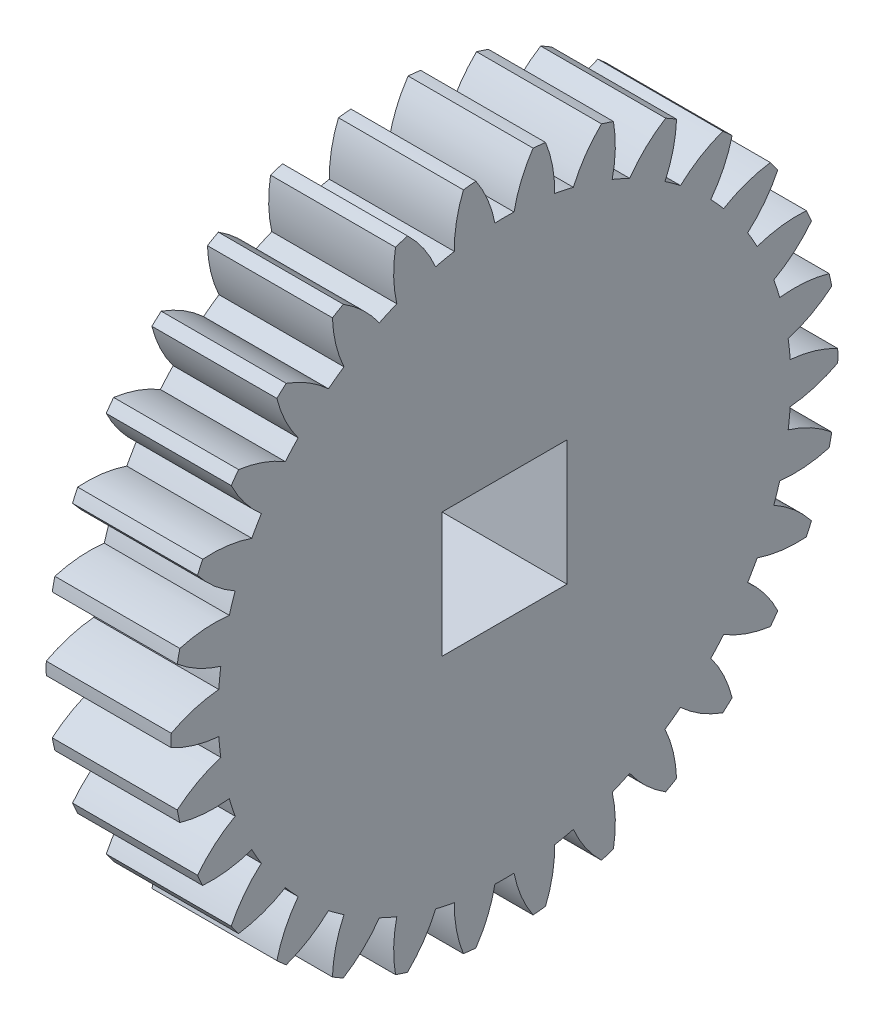
SolidWorks part; units mm, degrees
ref_plane "Plane1" through (0, 0, 0) normal (0, 0, 1) x (1, 0, 0)
ref_plane "Plane2" through (0, 0, 0) normal (0, 1, 0) x (1, 0, 0)
ref_plane "Plane3" through (0, 0, 0) normal (1, 0, 0) x (0, 0, -1)
sketch "HoldingSke" plane through (0, 0, 0) normal (0, 1, 0) x (1, 0, 0)
  line L0 (0, 0) -> (0.1732, -0.1)
  line L1 (-15, 0) -> (100, 0) construction
  line L2 (0, 0) -> (-2.1039, 2.3779)
  line L3 (0, 0) -> (-11.863, 4.5341)
  line L4 (0, 0) -> (7.479, 4.318)
  line L5 (0, 0) -> (-46.8476, -17.4728)
  line L6 (0, 0) -> (-13.2634, -8.9489)
  line L7 (-2.1039, 2.3779) -> (8.6586, 51.2059)
  line L8 (-76.2, 54.61) -> (-72.9, 54.61)
  line L9 (-71.009, 38.7566) -> (-53.1078, 45.2721)
  line L10 (-76.2, 71.12) -> (104.1128, 71.12)
  line L11 (0, 0) -> (-16, 0)
  line L12 (-76.2, 101.6) -> (-76.033, 101.6)
  line L13 (24.9733, 27.94) -> (52.9518, 28.4284)
  line L14 (24.9733, 27.94) -> (24.9743, 27.94)
  line L15 (24.9733, 27.94) -> (100.4006, 29.5858)
  line L16 (-63.627, -5) -> (-12.827, -5)
  circle A0 centre (0, 0) radius 13
  circle A1 centre (0, 0) radius 37.5
  circle A2 centre (0, 0) radius 37.5
  circle A3 centre (0, 0) radius 13
  dimension "MHD" = 75
  dimension "Hub_dia" = 75
  dimension "Bore" = 26
  dimension "MBD" = 26
  dimension "Num_teeth" = 30
  dimension "Pitch" = 0.2
  dimension "Overall_len" = 50
  dimension "Show_teeth" = 30
  dimension "Thickness" = 16
  dimension "OAL" = 50.0001
  dimension "T_dim" = 3.3
  dimension "Ap" = 20
  dimension "H" = 19.05
  dimension "Pitch_radius" = 180.3128
  dimension "Width" = 16
  dimension "Backlash" = 0.167
  dimension "Addendum_fac" = 1
  dimension "Dedendum_fac" = 1.25
  dimension "Clearance_fac" = 0.25
  dimension "Dedendum_add" = 0.001
  dimension "Module" = 5
sketch "BasProSke" plane through (0, 0, 0) normal (0, 1, 0) x (1, 0, 0)
  line L0 (-10, 0) -> (60, 0) construction
  line L1 (0, 0) -> (0, 80)
  line L2 (0, 0) -> (30, 0)
  line L3 (30, 0) -> (30, 80)
  line L4 (30, 80) -> (0, 80)
  dimension "Thickness" = 30
  dimension "Diameter" = 160
revolve "Base-Revolve" add sketch "BasProSke" angle 360 about L0
sketch "TooCutSke" plane through (0, 0, 0) normal (1, 0, 0) x (0, 0, -1)
  line L1 (0, 0) -> (0, 107) construction
  line L2 (0, 0) -> (-4.2174, 74.8813) construction
  line L3 (0, 0) -> (-15.6609, 149.0032) construction
  line L4 (-4.2174, 74.8813) -> (-7.8304, 74.5016) construction
  arc A0 (2.2959, 68.7107) -> (-2.2959, 68.7107) centre (0, 0) ccw
  arc A1 (6.8791, 79.7292) -> (-6.8791, 79.7292) centre (0, 0) ccw
  circle A2 centre (0, 0) radius 75 construction
  circle A3 centre (0, 0) radius 70.4769 construction
  arc A4 (-2.2959, 68.7107) -> (-6.8791, 79.7292) centre (-31.7334, 62.9285) ccw
  arc A5 (6.8791, 79.7292) -> (2.2959, 68.7107) centre (31.7334, 62.9285) ccw
  dimension "Root_dia" = 137.498
  dimension "Overcut_dia" = 160.0508
  dimension "Pitch_dia" = 150
  dimension "Base_dia" = 140.9539
  dimension "Flank_rad" = 30
  dimension "Half_ang" = 6
  dimension "Half_CT" = 3.6329
extrude "ToothCut" cut sketch "TooCutSke" along normal through all
fillet "Breaks" [suppressed] radius 0.1
fillet "RootFillets" [suppressed] radius 1.251
pattern_circular "TeethCuts" count 30 every 12 about axis through (-10, 0, 0) along (1, 0, 0) of "ToothCut", "RootFillets", "Breaks"
sketch "HubNeaOneSke" plane through (0, 0, 0) normal (-1, 0, 0) x (0, 0, 1)
  circle A0 centre (0, 0) radius 37.5
  dimension "Diameter" = 75
extrude "HubNearOne" [suppressed] add sketch "HubNeaOneSke" along normal blind 20.0001
sketch "HubNeaBotSke" plane through (0, 0, 0) normal (-1, 0, 0) x (0, 0, 1)
  circle A0 centre (0, 0) radius 37.5
  dimension "Diameter" = 75
extrude "HubNearBoth" [suppressed] add sketch "HubNeaBotSke" along normal blind 10
ref_plane "FarPln" through (30, 0, 0) normal (1, 0, 0) x (0, 0, -1)
sketch "HubFarSke" plane through (30, 0, 0) normal (1, 0, 0) x (0, 0, -1)
  circle A0 centre (0, 0) radius 37.5
  dimension "Diameter" = 75
extrude "HubFar" [suppressed] add sketch "HubFarSke" along normal blind 10
sketch "BorSke" plane through (0, 0, 0) normal (1, 0, 0) x (0, 0, -1)
  line L1 (15, -15) -> (-15, -15)
  line L2 (15, -15) -> (15, 15)
  line L3 (15, 15) -> (-15, 15)
  line L4 (-15, -15) -> (-15, 15)
  line L5 (15, -15) -> (-15, 15) construction
  line L6 (15, 15) -> (-15, -15) construction
  point P0 (0, 0)
  dimension "D1" = 30
  dimension "D2" = 30
extrude "Bore" cut sketch "BorSke" along normal mid plane 100.0001
sketch "KeySke" plane through (0, 0, 0) normal (1, 0, 0) x (0, 0, -1)
  line L0 (-4, 0) -> (-4, 16.3)
  line L1 (-4, 16.3) -> (4, 16.3)
  line L2 (4, 16.3) -> (4, 0)
  line L3 (0, 0) -> (0, 34) construction
  line L4 (-4, 0) -> (4, 0)
  dimension "Offset" = 16.3
  dimension "Width" = 8
extrude "Keyway" [suppressed] cut sketch "KeySke" along normal mid plane 100.0001
pattern_circular "Keyway2" [suppressed] count 2 every 90 about axis through (-10, 0, 0) along (1, 0, 0)
equation "' \"Module@HoldingSke\" = 6.35"
equation "' \"Num_teeth@HoldingSke\" = 12"
equation "' \"Ap@HoldingSke\" =  20"
equation "' \"Ap@HoldingSke\" = 20"
equation "' \"Width@HoldingSke\" = 0.5 * 25.4"
equation "' \"Hub_dia@HoldingSke\"= 1 * 25.4"
equation "' \"Hub_dia@HoldingSke\" = 1 * 25.4"
equation "' \"Overall_len@HoldingSke\" = 1.0 * 25.4"
equation "' \"Bore@HoldingSke\" = 0.75 * 25.4"
equation "' \"T_dim@HoldingSke\" = 0.1 * 25.4"
equation "' \"Width@KeySke\" = 0.25 * 25.4"
equation "' \"Show_teeth@HoldingSke\" = 13"
equation "' \"Backlash@HoldingSke\" = 0.009 * 25.4"
equation "' \"Addendum_fac@HoldingSke\" = 1.0"
equation "' \"Dedendum_fac@HoldingSke\" = 1.25"
equation "' \"Dedendum_add@HoldingSke\" = 0.00005 * 25.4"
equation "' \"Clearance_fac@HoldingSke\" = 0.25"
equation "\"Pitch@HoldingSke\" = 1 / \"Module@HoldingSke\""
equation "\"Overcut_dia@TooCutSke\" = (\"Num_teeth@HoldingSke\" + 2 * \"Addendum_fac@HoldingSke\") / \"Pitch@HoldingSke\" + 0.002 * 25.4"
equation "\"Pitch_dia@TooCutSke\" = \"Num_teeth@HoldingSke\" / \"Pitch@HoldingSke\""
equation "\"Base_dia@TooCutSke\" = \"Num_teeth@HoldingSke\" / \"Pitch@HoldingSke\" * cos((\"Ap@HoldingSke\"  * 3.14159265 / 180))"
equation "\"Root_dia@TooCutSke\" = (\"Num_teeth@HoldingSke\" + 2) / \"Pitch@HoldingSke\" - 2 * (\"Addendum_fac@HoldingSke\" + \"Dedendum_fac@HoldingSke\") / \"Pitch@HoldingSke\" - \"Dedendum_add@HoldingSke\" * 2"
equation "\"Half_ang@TooCutSke\" = 180 / \"Num_teeth@HoldingSke\""
equation "\"Half_CT@TooCutSke\" = \"Num_teeth@HoldingSke\" / \"Pitch@HoldingSke\" * sin((3.14159265 / 2 / \"Num_teeth@HoldingSke\")) / 2 - 7 * \"Backlash@HoldingSke\" / 4"
equation "\"Flank_rad@TooCutSke\" = \"Num_teeth@HoldingSke\" / \"Pitch@HoldingSke\" / 5"
equation "\"Radius@RootFillets\" = \"Clearance_fac@HoldingSke\" / \"Pitch@HoldingSke\" + \"Dedendum_add@HoldingSke\""
equation "\"Break_rad@Breaks\" = 0.02 / \"Pitch@HoldingSke\""
equation "\"Thickness@HoldingSke\" = \"Width@HoldingSke\""
equation "\"OAL@HoldingSke\" = \"Thickness@HoldingSke\""
equation "\"MHD@HoldingSke\" = (\"Num_teeth@HoldingSke\" + 2) / \"Pitch@HoldingSke\" - 2 * (\"Addendum_fac@HoldingSke\" + \"Dedendum_fac@HoldingSke\")  / \"Pitch@HoldingSke\" - \"Dedendum_add@HoldingSke\" * 2"
equation "\"MBD@HoldingSke\" = (\"Num_teeth@HoldingSke\" + 2) / \"Pitch@HoldingSke\" - 2 * (\"Addendum_fac@HoldingSke\" + \"Dedendum_fac@HoldingSke\")  / \"Pitch@HoldingSke\" - \"Dedendum_add@HoldingSke\" * 2 - 0.002 * 25.4"
equation "\"MHD@HoldingSke\" = ((sgn( \"MHD@HoldingSke\" - \"Hub_dia@HoldingSke\" )-1)*( \"MHD@HoldingSke\" - \"Hub_dia@HoldingSke\" ))/-2+ \"Hub_dia@HoldingSke\""
equation "\"MBD@HoldingSke\" = ((sgn( \"MBD@HoldingSke\" - \"Bore@HoldingSke\" )-1)*( \"MBD@HoldingSke\" - \"Bore@HoldingSke\" ))/-2+ \"Bore@HoldingSke\""
equation "\"OAL@HoldingSke\" = ((sgn( \"OAL@HoldingSke\" - \"Overall_len@HoldingSke\" )+1)*( \"OAL@HoldingSke\" - \"Overall_len@HoldingSke\" ))/2 + \"Overall_len@HoldingSke\" + 0.000002 * 25.4"
equation "\"Num_teeth@TeethCuts\" = int( \"Show_teeth@HoldingSke\" ) + 1"
equation "\"Num_teeth@TeethCuts\" = ((sgn( \"Num_teeth@TeethCuts\" - \"Num_teeth@HoldingSke\" )-1)*( \"Num_teeth@TeethCuts\" - \"Num_teeth@HoldingSke\" ))/-2+ \"Num_teeth@HoldingSke\""
equation "\"Num_teeth@TeethCuts\" = ((sgn( \"Num_teeth@TeethCuts\" - 2.0)+1)*( \"Num_teeth@TeethCuts\" - 2.0))/2 +2.0"
equation "\"Angle@TeethCuts\" = 360.0 / \"Num_teeth@HoldingSke\""
equation "\"Diameter@BasProSke\" = (\"Num_teeth@HoldingSke\" + 2 * \"Addendum_fac@HoldingSke\") / \"Pitch@HoldingSke\""
equation "' \"Fillet_rad@BasProSke\" =  \"Thickness@HoldingSke\" * 0.05"
equation "' \"Fillet_rad@BasProSke\" = \"Thickness@HoldingSke\" * 0.05"
equation "\"MHD@HoldingSke\" = ((sgn( \"MHD@HoldingSke\" - \"Root_dia@TooCutSke\" )-1)*( \"MHD@HoldingSke\" - \"Root_dia@TooCutSke\" ))/-2+ \"Root_dia@TooCutSke\""
equation "\"Diameter@HubNeaOneSke\" = \"MHD@HoldingSke\""
equation "\"Length@HubNearOne\" = \"OAL@HoldingSke\" - \"Thickness@BasProSke\""
equation "\"Diameter@HubNeaBotSke\" = \"MHD@HoldingSke\""
equation "\"Length@HubNearBoth\" = ( \"OAL@HoldingSke\" - \"Thickness@BasProSke\" ) / 2.0"
equation "\"Thickness@FarPln\" = \"Thickness@BasProSke\""
equation "\"Diameter@HubFarSke\" = \"MHD@HoldingSke\""
equation "\"Length@HubFar\" = ( \"OAL@HoldingSke\" - \"Thickness@BasProSke\" ) / 2.0"
equation "\"D1@Bore\" = \"OAL@HoldingSke\" * 2.0"
equation "\"D1@Keyway\" = \"OAL@HoldingSke\" * 2.0"
equation "\"Offset@KeySke\" = \"T_dim@HoldingSke\" + \"MBD@HoldingSke\" / 2.0"
